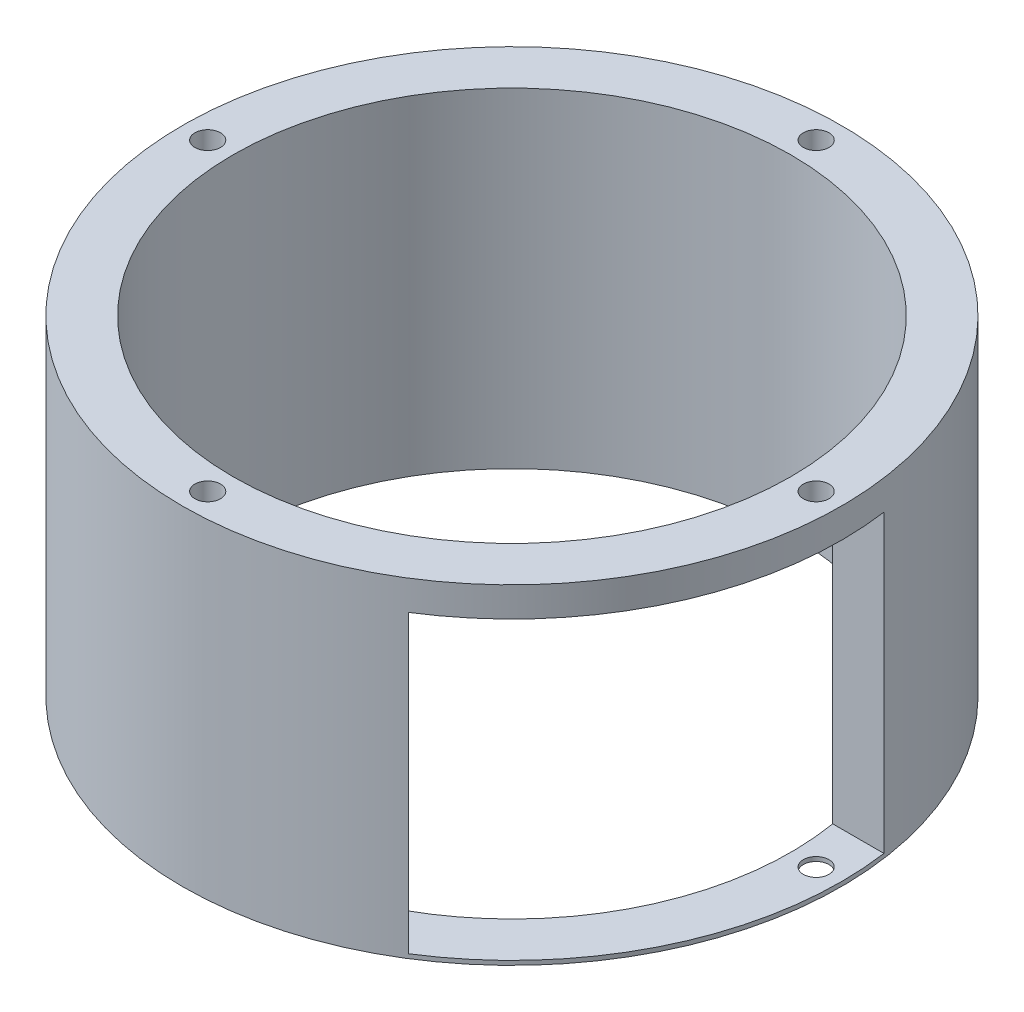
SolidWorks part; units mm, degrees
ref_plane "Front Plane" through (0, 0, 0) normal (0, 0, 1) x (1, 0, 0)
ref_plane "Top Plane" through (0, 0, 0) normal (0, 1, 0) x (1, 0, 0)
ref_plane "Right Plane" through (0, 0, 0) normal (1, 0, 0) x (0, 0, -1)
sketch "Sketch1" plane through (0, 0, 0) normal (0, 1, 0) x (1, 0, 0)
  line L0 (0, 55) -> (0, 65) construction
  arc A0 (0, 65) -> (0, -65) centre (0, 0) ccw
  circle A2 centre (0, 60) radius 2.525
  circle A3 centre (60, 0) radius 2.525
  circle A4 centre (0, -60) radius 2.525
  circle A5 centre (-60, 0) radius 2.525
  circle A6 centre (0, 0) radius 65
  circle A7 centre (0, 0) radius 55
  point P18 (0, 0)
  dimension "D1" = 130
  dimension "D3" = 5.05
  dimension "D2" = 10
  dimension "D4" = 4
extrude "Boss-Extrude1" add sketch "Sketch1" along normal blind 65
sketch "Sketch2" plane through (0, 0, 0) normal (1, 0, 0) x (0, 0, -1)
  line L2 (-65, 0) -> (65, 0) construction
  line L3 (65, 65) -> (-65, 65) construction
  line L6 (65, 0) -> (65, 65)
  line L7 (-65, 65) -> (-65, 0)
  line L8 (0, 75) -> (0, 30)
  line L9 (0, 30) -> (-24.25, 30)
  line L10 (-65, 0) -> (65, 0)
  line L11 (65, 65) -> (-65, 65)
  circle A0 centre (-24.25, 30) radius 9.525
  dimension "D3" = 19.05
  dimension "D1" = 24.25
  dimension "D2" = 45
extrude "Cut-Extrude1" cut sketch "Sketch2" along normal through all contours A0
sketch "Sketch3" plane through (0, 0, 0) normal (1, 0, 0) x (0, 0, -1)
  line L2 (-41.625, 43.85) -> (-41.625, 53.85)
  line L3 (-48.125, 53.85) -> (-48.125, 43.85)
  line L4 (-55, 0.85) -> (9, 0.85)
  line L5 (-55, 59.15) -> (-55, 0.85)
  line L6 (9, 59.15) -> (-55, 59.15)
  line L7 (9, 0.85) -> (9, 59.15)
  line L8 (-55, 0.85) -> (9, 0.85)
  line L9 (-55, 59.15) -> (-55, 0.85)
  line L10 (9, 59.15) -> (-55, 59.15)
  line L11 (9, 0.85) -> (9, 59.15)
  line L12 (-41.625, 43.85) -> (-41.625, 53.85)
  line L13 (-48.125, 53.85) -> (-48.125, 43.85)
  line L14 (2.125, 43.85) -> (2.125, 53.85)
  line L15 (-4.375, 53.85) -> (-4.375, 43.85)
  line L16 (2.125, 43.85) -> (2.125, 53.85)
  line L17 (-4.375, 53.85) -> (-4.375, 43.85)
  circle A1 centre (-44.875, 53.85) radius 3.25
  circle A2 centre (-44.875, 53.85) radius 3.25
  circle A3 centre (-1.125, 53.85) radius 3.25
  circle A4 centre (-1.125, 53.85) radius 3.25
  arc A6 (-48.125, 43.85) -> (-41.625, 43.85) centre (-44.875, 43.85) ccw
  arc A7 (-41.625, 53.85) -> (-48.125, 53.85) centre (-44.875, 53.85) ccw
  arc A8 (-48.125, 43.85) -> (-41.625, 43.85) centre (-44.875, 43.85) ccw
  arc A9 (-41.625, 53.85) -> (-48.125, 53.85) centre (-44.875, 53.85) ccw
  arc A10 (-4.375, 43.85) -> (2.125, 43.85) centre (-1.125, 43.85) ccw
  arc A11 (2.125, 53.85) -> (-4.375, 53.85) centre (-1.125, 53.85) ccw
  arc A12 (-4.375, 43.85) -> (2.125, 43.85) centre (-1.125, 43.85) ccw
  arc A13 (2.125, 53.85) -> (-4.375, 53.85) centre (-1.125, 53.85) ccw
  dimension "D1" = 0
  dimension "D2" = 0
  dimension "D3" = 0
  dimension "D4" = 0
  dimension "D5" = 0
extrude "Cut-Extrude2" cut sketch "Sketch3" along normal through all contours L12 A9 L13 A8 | L16 A13 L17 A12 | L8 L11 L10 L9
